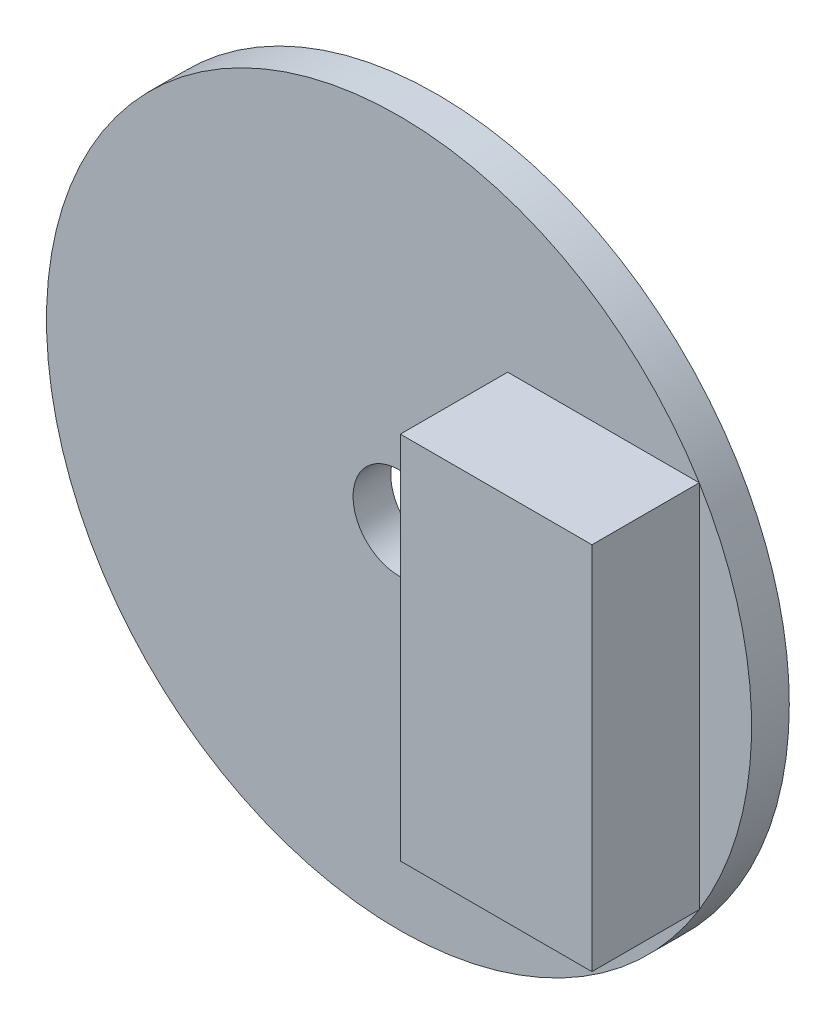
SolidWorks part; units mm, degrees
material "Power Circuit Board"
ref_plane "Alzado" through (0, 0, 0) normal (0, 0, 1) x (1, 0, 0)
ref_plane "Planta" through (0, 0, 0) normal (0, 1, 0) x (1, 0, 0)
ref_plane "Vista lateral" through (0, 0, 0) normal (1, 0, 0) x (0, 0, -1)
sketch "Sketch1" plane through (0, 0, 0) normal (0, 0, 1) x (1, 0, 0)
  circle A0 centre (0, 0) radius 11.5
  dimension "D1" = 23
extrude "Boss-Extrude1" add sketch "Sketch1" along normal blind 1.23
sketch "Sketch2" plane through (0, 0, 1.23) normal (0, 0, 1) x (1, 0, 0)
  line L0 (-11.5, 0) -> (11.5, 0) construction
  line L1 (9.7925, 6.0297) -> (3.5425, 6.0297)
  line L2 (9.7925, 6.0297) -> (9.7925, -6.0297)
  line L3 (9.7925, -6.0297) -> (3.5425, -6.0297)
  line L4 (3.5425, 6.0297) -> (3.5425, -6.0297)
  circle A0 centre (0, 0) radius 11.5 construction
  point P9 (3.5425, 0)
  dimension "D1" = 6.25
extrude "Boss-Extrude2" add sketch "Sketch2" along normal blind 3.5
sketch "Sketch3" plane through (0, 0, 1.23) normal (0, 0, 1) x (1, 0, 0)
  circle A0 centre (0, 0) radius 1.5
  dimension "D1" = 3
extrude "Cut-Extrude1" cut sketch "Sketch3" against normal through all
